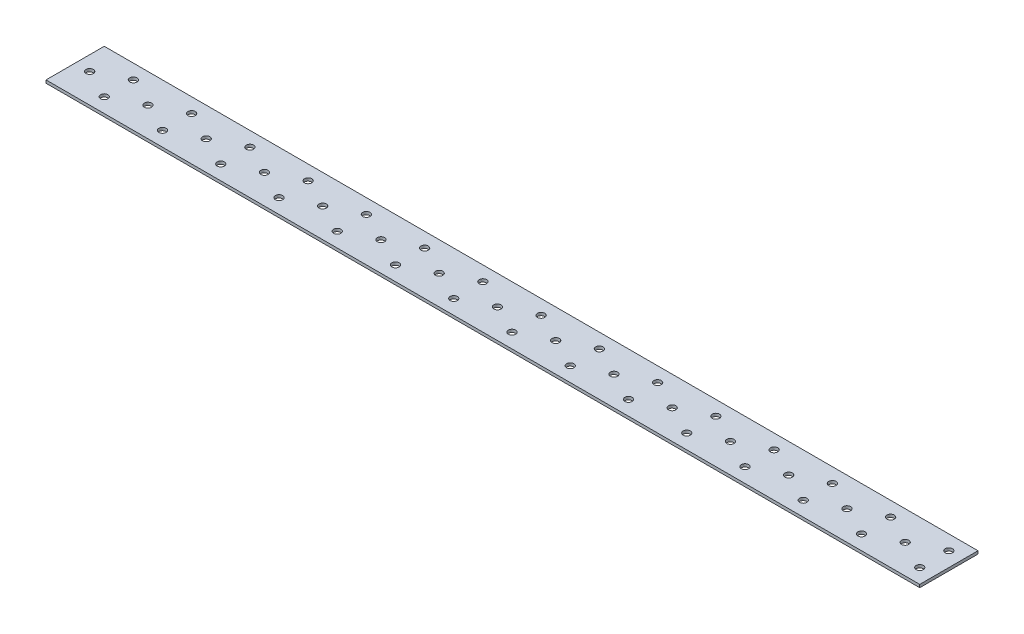
SolidWorks part; units mm, degrees
ref_plane "Спереди" through (0, 0, 0) normal (0, 0, 1) x (1, 0, 0)
ref_plane "Сверху" through (0, 0, 0) normal (0, 1, 0) x (1, 0, 0)
ref_plane "Справа" through (0, 0, 0) normal (1, 0, 0) x (0, 0, -1)
sketch "Эскиз1" plane through (0, 0, 0) normal (0, 1, 0) x (1, 0, 0)
  line L0 (-300, 0) -> (300, 0) construction
  line L1 (300, 20) -> (-300, 20)
  line L2 (300, 20) -> (300, -20)
  line L3 (300, -20) -> (-300, -20)
  line L4 (-300, 20) -> (-300, -20)
  line L5 (300, 20) -> (-300, -20) construction
  line L6 (300, -20) -> (-300, 20) construction
  line L7 (-270, 10) -> (-230, 10) construction
  circle A0 centre (-290, 0) radius 2.5
  circle A1 centre (-270, 10) radius 2.5
  circle A2 centre (-270, -10) radius 2.5
  circle A3 centre (-230, 10) radius 2.5
  circle A4 centre (-230, -10) radius 2.5
  circle A5 centre (-250, 0) radius 2.5
  circle A6 centre (-190, 10) radius 2.5
  circle A7 centre (-190, -10) radius 2.5
  circle A8 centre (-210, 0) radius 2.5
  circle A9 centre (-150, 10) radius 2.5
  circle A10 centre (-150, -10) radius 2.5
  circle A11 centre (-170, 0) radius 2.5
  circle A12 centre (-110, 10) radius 2.5
  circle A13 centre (-110, -10) radius 2.5
  circle A14 centre (-130, 0) radius 2.5
  circle A15 centre (-70, 10) radius 2.5
  circle A16 centre (-70, -10) radius 2.5
  circle A17 centre (-90, 0) radius 2.5
  circle A18 centre (-30, 10) radius 2.5
  circle A19 centre (-30, -10) radius 2.5
  circle A20 centre (-50, 0) radius 2.5
  circle A21 centre (10, 10) radius 2.5
  circle A22 centre (10, -10) radius 2.5
  circle A23 centre (-10, 0) radius 2.5
  circle A24 centre (50, 10) radius 2.5
  circle A25 centre (50, -10) radius 2.5
  circle A26 centre (30, 0) radius 2.5
  circle A27 centre (90, 10) radius 2.5
  circle A28 centre (90, -10) radius 2.5
  circle A29 centre (70, 0) radius 2.5
  circle A30 centre (130, 10) radius 2.5
  circle A31 centre (130, -10) radius 2.5
  circle A32 centre (110, 0) radius 2.5
  circle A33 centre (170, 10) radius 2.5
  circle A34 centre (170, -10) radius 2.5
  circle A35 centre (150, 0) radius 2.5
  circle A36 centre (210, 10) radius 2.5
  circle A37 centre (210, -10) radius 2.5
  circle A38 centre (190, 0) radius 2.5
  circle A39 centre (250, 10) radius 2.5
  circle A40 centre (250, -10) radius 2.5
  circle A41 centre (230, 0) radius 2.5
  circle A42 centre (290, 10) radius 2.5
  circle A43 centre (290, -10) radius 2.5
  circle A44 centre (270, 0) radius 2.5
  point P0 (0, 0)
  dimension "D4" = 5
  dimension "D5" = 5
  dimension "D1" = 40
  dimension "D2" = 600
  dimension "D3" = 10
  dimension "D6" = 20
  dimension "D7" = 20
  dimension "D9" = 40
  dimension "D8" = 15
extrude "Бобышка-Вытянуть1" add sketch "Эскиз1" along normal blind 2
equation "\"D5@Эскиз1\"=\"D4@Эскиз1\""
